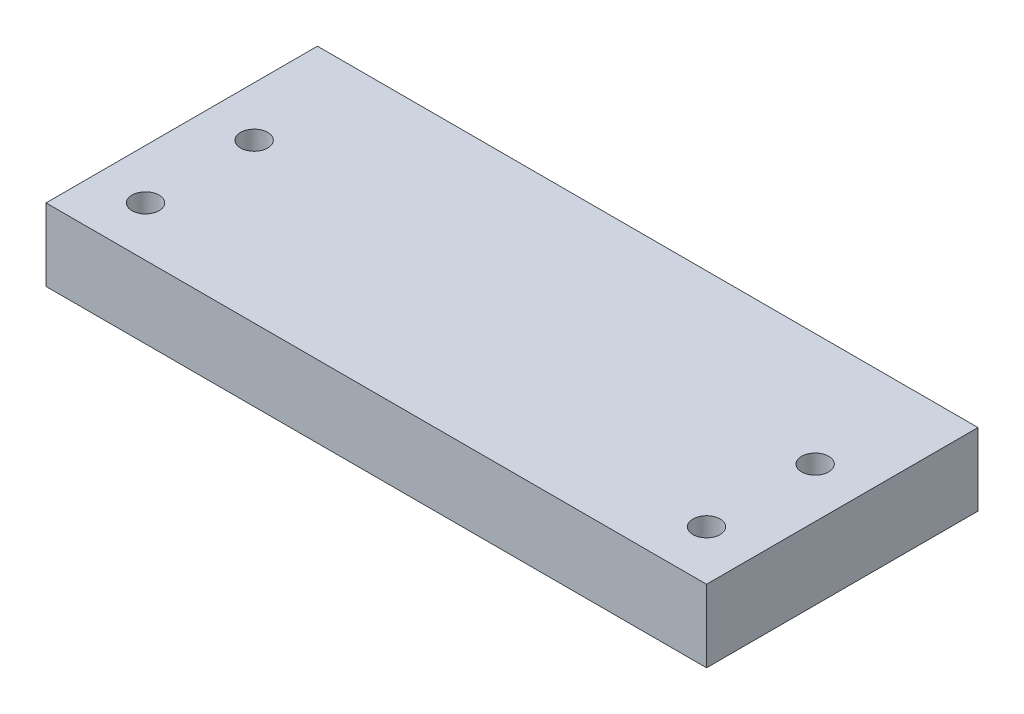
SolidWorks part; units mm, degrees
material "橡胶"
ref_plane "前视基准面" through (0, 0, 0) normal (0, 0, 1) x (1, 0, 0)
ref_plane "上视基准面" through (0, 0, 0) normal (0, 1, 0) x (1, 0, 0)
ref_plane "右视基准面" through (0, 0, 0) normal (1, 0, 0) x (0, 0, -1)
sketch "草图1" plane through (0, 0, 0) normal (0, 1, 0) x (1, 0, 0)
  line L1 (-36.5, -15) -> (36.5, -15)
  line L2 (-36.5, -15) -> (-36.5, 15)
  line L3 (-36.5, 15) -> (36.5, 15)
  line L4 (36.5, -15) -> (36.5, 15)
  line L5 (-36.5, -15) -> (36.5, 15) construction
  line L6 (-36.5, 15) -> (36.5, -15) construction
  point P0 (0, 0)
  dimension "D1" = 73
  dimension "D2" = 30
extrude "凸台-拉伸1" add sketch "草图1" along normal blind 8
extrude "切除-拉伸1" cut sketch "草图2" against normal mid plane 90
sketch "草图2" plane through (59.2821, -28, -16.5) normal (0, -1, 0) x (1, 0, 0)
  line L0 (-59.2821, -13) -> (-59.2821, 41) construction
  circle A2 centre (-28.2821, 14) radius 1.5
  circle A3 centre (-90.2821, 14) radius 1.5
  circle A6 centre (-90.2821, 26) radius 1.5
  circle A7 centre (-28.2821, 26) radius 1.5
